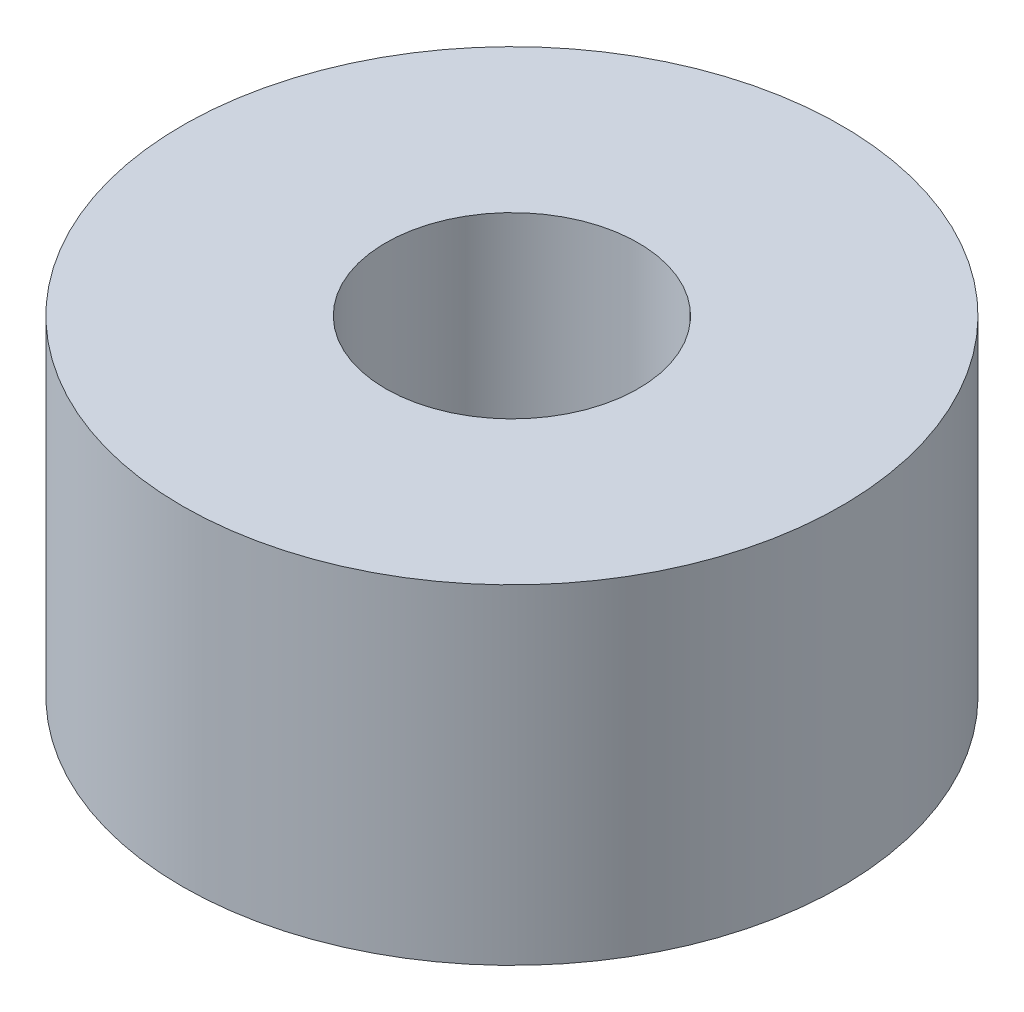
SolidWorks part; units mm, degrees
ref_plane "前视基准面" through (0, 0, 0) normal (0, 0, 1) x (1, 0, 0)
ref_plane "上视基准面" through (0, 0, 0) normal (0, 1, 0) x (1, 0, 0)
ref_plane "右视基准面" through (0, 0, 0) normal (1, 0, 0) x (0, 0, -1)
other "Configuration Table"
sketch "草图1" plane through (0, 0, 0) normal (0, 1, 0) x (1, 0, 0)
  circle A0 centre (0, 0) radius 1.15
  circle A1 centre (0, 0) radius 3
  dimension "D1" = 2.3
  dimension "D2" = 6
extrude "凸台-拉伸1" add sketch "草图1" along normal blind 3
